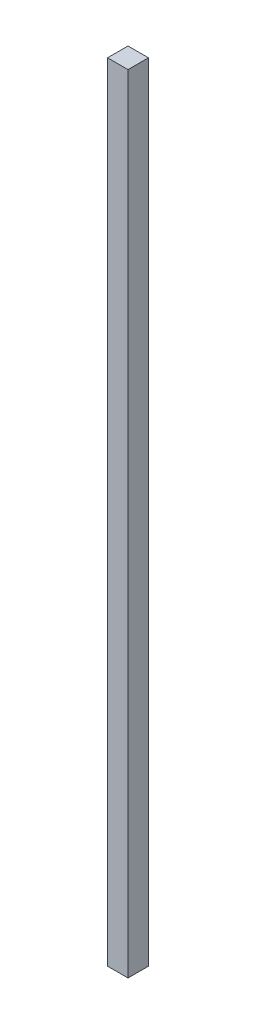
SolidWorks part; units mm, degrees
material "Balsa"
ref_plane "Front Plane" through (0, 0, 0) normal (0, 0, 1) x (1, 0, 0)
ref_plane "Top Plane" through (0, 0, 0) normal (0, 1, 0) x (1, 0, 0)
ref_plane "Right Plane" through (0, 0, 0) normal (1, 0, 0) x (0, 0, -1)
sketch "Sketch1" plane through (0, 0, 0) normal (0, 1, 0) x (1, 0, 0)
  line L1 (0, 0) -> (6.35, 0)
  line L2 (0, 0) -> (0, -6.35)
  line L3 (0, -6.35) -> (6.35, -6.35)
  line L4 (6.35, 0) -> (6.35, -6.35)
  dimension "D1" = 6.35
  dimension "D2" = 6.35
extrude "Boss-Extrude1" add sketch "Sketch1" along normal blind 244.348
